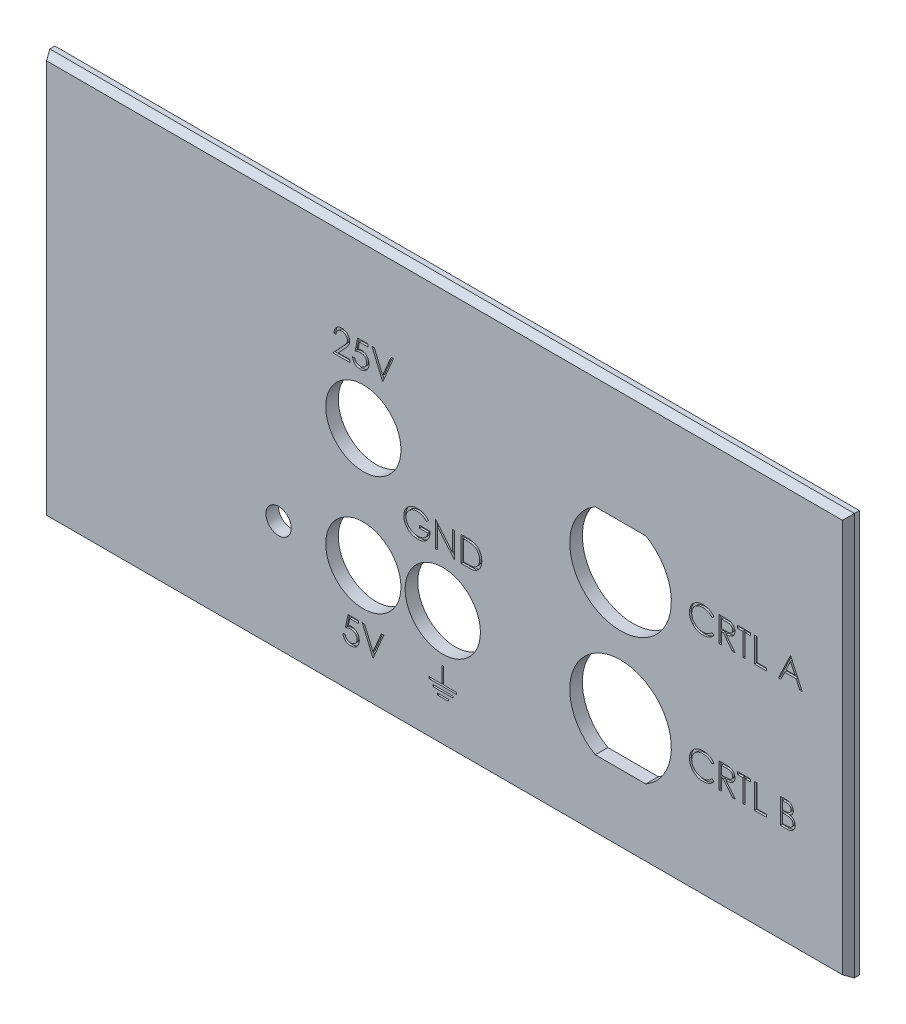
SolidWorks part; units mm, degrees
ref_plane "Front Plane" through (0, 0, 0) normal (0, 0, 1) x (1, 0, 0)
ref_plane "Top Plane" through (0, 0, 0) normal (0, 1, 0) x (1, 0, 0)
ref_plane "Right Plane" through (0, 0, 0) normal (1, 0, 0) x (0, 0, -1)
sketch "Sketch1" plane through (0, 0, 0) normal (0, 0, 1) x (1, 0, 0)
  line L0 (0, 25.4) -> (0, -25.4)
  line L1 (-50.8, 0) -> (50.8, 0)
  point P4 (0, 0)
  point P8 (0, 0)
  dimension "Width" = 101.6
  dimension "Height" = 50.8
sketch "Sketch2" plane through (0, 0, 0) normal (1, 0, 0) x (0, 0, -1)
  line L0 (-0.7937, 0) -> (0.7937, 0)
  point P3 (0, 0)
ref_plane "Plane1" through (0, 0, -0.7937) normal (0, 0, 1) x (1, 0, 0)
sketch "Sketch3" plane through (0, 0, -0.7937) normal (0, 0, 1) x (1, 0, 0)
  line L1 (-50.8, 25.4) -> (50.8, 25.4)
  line L2 (-50.8, 25.4) -> (-50.8, -25.4)
  line L3 (-50.8, -25.4) -> (50.8, -25.4)
  line L4 (50.8, 25.4) -> (50.8, -25.4)
extrude "Boss-Extrude1" add sketch "Sketch3" along normal blind 0.635
sketch "Sketch4" plane through (0, 0, -0.1587) normal (0, 0, 1) x (1, 0, 0)
  line L4 (-50.8, 25.4) -> (-50.8, -25.4)
  line L5 (-50.8, -25.4) -> (50.8, -25.4)
  line L6 (50.8, -25.4) -> (50.8, 25.4)
  line L7 (50.8, 25.4) -> (-50.8, 25.4)
  line L8 (-50.8, 25.4) -> (-50.8, -25.4)
  line L9 (-50.8, -25.4) -> (50.8, -25.4)
  line L10 (50.8, -25.4) -> (50.8, 25.4)
  line L11 (50.8, 25.4) -> (-50.8, 25.4)
  dimension "D1" = 0
extrude "Boss-Extrude2" add sketch "Sketch4" along normal up to vertex (0.9525 mm away) draft 30 up to point (0, 0, 0.7937)
sketch "Sketch5" plane through (0, 0, 0.7937) normal (0, 0, 1) x (1, 0, 0)
  line L0 (19.0327, 10.7271) -> (25.4173, 10.7271)
  line L1 (25.4173, -16.3976) -> (19.0327, -16.3976)
  arc A0 (19.0327, 10.7271) -> (25.4173, 10.7271) centre (22.225, 5.1645) ccw
  arc A1 (25.4173, -16.3976) -> (19.0327, -16.3976) centre (22.225, -10.835) ccw
  circle A2 centre (-10.254, 4.6686) radius 4.75
  circle A3 centre (-10.254, -10.3314) radius 4.75
  circle A4 centre (-0.2214, -10.2764) radius 4.75
  point P0 (-10.254, -10.3314)
  point P1 (-10.254, 4.6686)
  point P3 (-0.2214, -10.2764)
  point P5 (22.225, -10.835)
  point P7 (22.225, 5.1645)
  point P9 (-20.955, -10.8314)
  point P20 (20.936, 13.097)
extrude "Cut-Extrude1" cut sketch "Sketch5" against normal through all both and the other way through all
hole_wizard "M3 Clearance Hole1" positions "Sketch6" profile "Sketch7" hole size "M3" standard "ANSI Metric" end condition through all
sketch "Sketch6" plane through (0, 0, 0.7937) normal (0, 0, 1) x (1, 0, 0)
  point P0 (-20.955, -10.8314)
sketch "Sketch7" plane through (-20.955, -10.8314, 0.7937) normal (1, 0, 0) x (0, -1, 0)
  line L0 (0, 0) -> (0, 1.5875)
  line L1 (0, 1.5875) -> (1.6, 1.5875)
  line L2 (1.6, 1.5875) -> (1.6, 0)
  line L5 (1.6, 0) -> (0, 0)
  line L11 (0, -6.35) -> (0, 107.95) construction
  dimension "Thru Hole Dia." = 3.2
  dimension "Thru Hole Depth" = 1.5875
sketch "Sketch9" plane through (0, 0, 0.7937) normal (0, 0, 1) x (1, 0, 0)
  line L0 (22.225, 5.1645) -> (22.225, 3.577) construction
  line L1 (22.225, -10.835) -> (22.225, -12.4225) construction
  line L2 (22.225, -12.4225) -> (30.6836, -12.4225) construction
  line L3 (30.6836, -12.4225) -> (43.8206, -12.4225) construction
  line L4 (22.225, 3.577) -> (30.6836, 3.577) construction
  line L5 (30.6836, 3.577) -> (43.8206, 3.577) construction
  line L6 (-10.254, -10.3314) -> (-10.254, -15.0814) construction
  line L7 (-10.254, -15.0814) -> (-10.254, -19.8439) construction
  line L8 (-14.3162, -19.8439) -> (-6.1918, -19.8439) construction
  line L9 (-10.254, 4.6686) -> (-10.254, 9.4186) construction
  line L10 (-10.254, 9.4186) -> (-10.254, 11.0061) construction
  line L11 (-14.3162, 11.0061) -> (-6.1918, 11.0061) construction
  line L12 (-0.2214, -10.2764) -> (-0.2214, -15.0264) construction
  line L13 (-0.2214, -15.0264) -> (-0.2214, -21.3679) construction
  line L14 (-4.2836, -21.3679) -> (3.8408, -21.3679) construction
  line L15 (-0.2214, -10.2764) -> (-0.2214, -5.5264) construction
  line L16 (-0.2214, -5.5264) -> (-0.2214, -3.9389) construction
  line L17 (-6.1918, -3.9389) -> (5.749, -3.9389) construction
  circle A0 centre (22.225, 5.1645) radius 8.2 construction
  circle A1 centre (22.225, -10.835) radius 8.2 construction
  circle A2 centre (-10.254, -10.3314) radius 4.75 construction
  circle A3 centre (-10.254, 4.6686) radius 4.75 construction
  circle A4 centre (-0.2214, -10.2764) radius 4.75 construction
  text T0 "CRTL B\r\n"
  text T1 "CRTL A"
  text T2 "5V"
  text T3 "25V"
  text T4 "G" font "Electronics Symbols" height in points 36
  text T5 "GND"
  point P23 (-10.254, -19.8439)
  point P31 (-10.254, 11.0061)
  point P43 (-0.2214, -21.3679)
  point P46 (-0.2214, -3.9389)
  point P48 (-6.1918, -3.9389)
extrude "Cut-Extrude2" cut sketch "Sketch9" against normal blind 0.254 and the other way through all
equation "\"D1@Boss-Extrude1\"=\"Thickness@Sketch2\"/2.5"
equation "\"D7@Sketch5\"=9.5mm"
equation "\"TextOffset\"= 1 / 16 * 1in"
equation "\"D2@Sketch9\"=\"TextOffset\""
